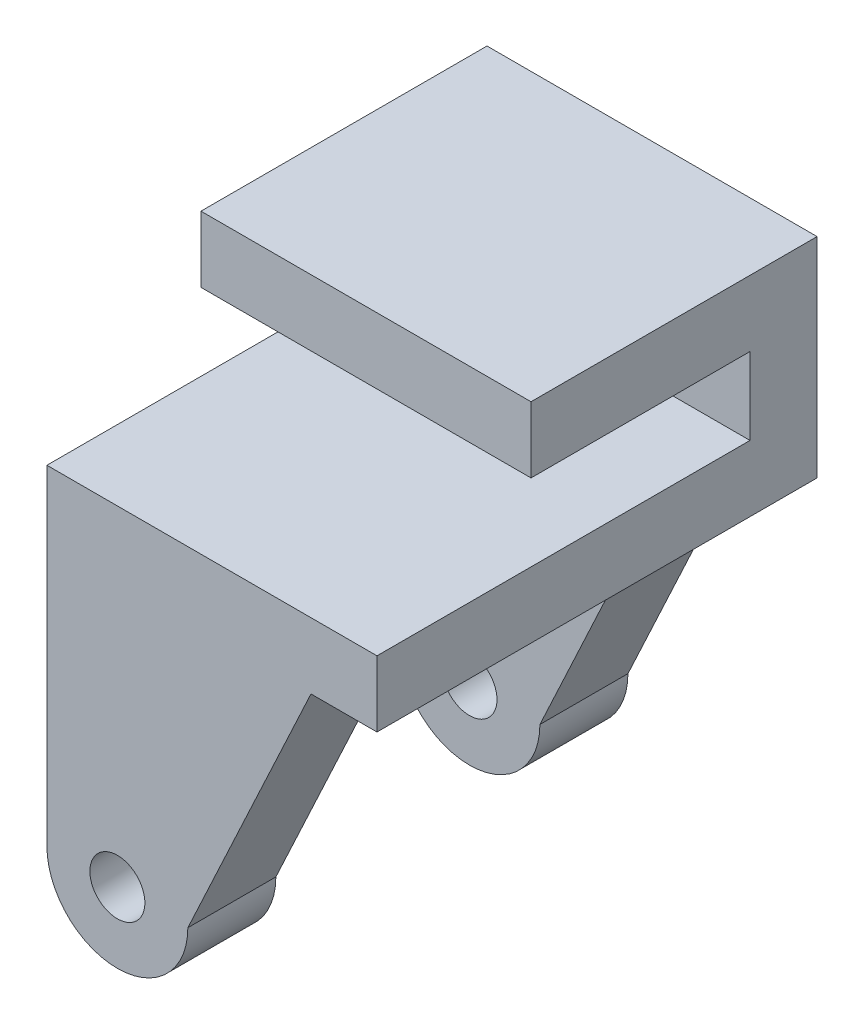
SolidWorks part; units mm, degrees
ref_plane "Front Plane" through (0, 0, 0) normal (0, 0, 1) x (1, 0, 0)
ref_plane "Top Plane" through (0, 0, 0) normal (0, 1, 0) x (1, 0, 0)
ref_plane "Right Plane" through (0, 0, 0) normal (1, 0, 0) x (0, 0, -1)
sketch "Sketch1" plane through (0, 0, 0) normal (1, 0, 0) x (0, 0, -1)
  line L1 (0, 0) -> (20, 0)
  line L2 (0, 0) -> (0, 9.5)
  line L3 (0, 9.5) -> (20, 9.5)
  line L4 (20, 0) -> (20, 9.5)
  dimension "D1" = 9.5
  dimension "D2" = 20
extrude "Boss-Extrude1" add sketch "Sketch1" along normal blind 15 contours L3 L4 L1 L2
sketch "Sketch2" plane through (15, 0, 0) normal (1, 0, 0) x (0, 0, -1)
  line L0 (20, 0) -> (20, 9.5) construction
  line L1 (20, 3) -> (3.0475, 3)
  line L2 (20, 3) -> (20, 6.3375)
  line L3 (13, 6.5) -> (3.0475, 6.5)
  line L4 (3.0475, 3) -> (3.0475, 6.5)
  line L6 (0, 9.5) -> (20, 9.5) construction
  line L9 (13, 6.5) -> (13, 9.5)
  line L10 (13, 9.5) -> (20, 9.5)
  line L11 (20, 6.3375) -> (20, 9.5)
  dimension "D1" = 3.5
  dimension "D2" = 3
  dimension "D3" = 7
extrude "Cut-Extrude1" cut sketch "Sketch2" against normal through all and the other way through all
sketch "Sketch4" plane through (0, 0, 0) normal (0, 0, 1) x (1, 0, 0)
  line L0 (0, 0) -> (0, -12)
  line L1 (12, 0) -> (6.4043, -12)
  line L2 (15, 0) -> (0, 0) construction
  line L3 (0, 0) -> (12, 0)
  arc A0 (0, -12) -> (6.4043, -12) centre (3.2022, -12) ccw
  circle A1 centre (3.2022, -12) radius 1.25
  dimension "D3" = 2.5
  dimension "D4" = 12
  dimension "D1" = 12
  dimension "D2" = 115
extrude "Boss-Extrude3" add sketch "Sketch4" against normal blind 4
ref_plane "Plane1" through (0, 0, -10) normal (0, 0, 1) x (1, 0, 0)
mirror "Mirror1" about plane through (0, 0, -10) normal (0, 0, 1) of "Boss-Extrude3"
mirror "Mirror2" about plane through (15, 0, -20) normal (0, 0, 1) of "Mirror1", "Boss-Extrude3", "Cut-Extrude1", "Boss-Extrude1"
ref_plane "Plane2" through (0, 0, -20) normal (0, 0, 1) x (1, 0, 0)
sketch "Sketch5" plane through (0, 0, -20) normal (0, 0, 1) x (1, 0, 0)
  line L1 (-0.3001, -15.6817) -> (15.2625, -15.6817)
  line L2 (-0.3001, -15.6817) -> (-0.3001, 9.8665)
  line L3 (-0.3001, 9.8665) -> (15.2625, 9.8665)
  line L4 (15.2625, -15.6817) -> (15.2625, 9.8665)
extrude "Cut-Extrude2" cut sketch "Sketch5" along normal through all
